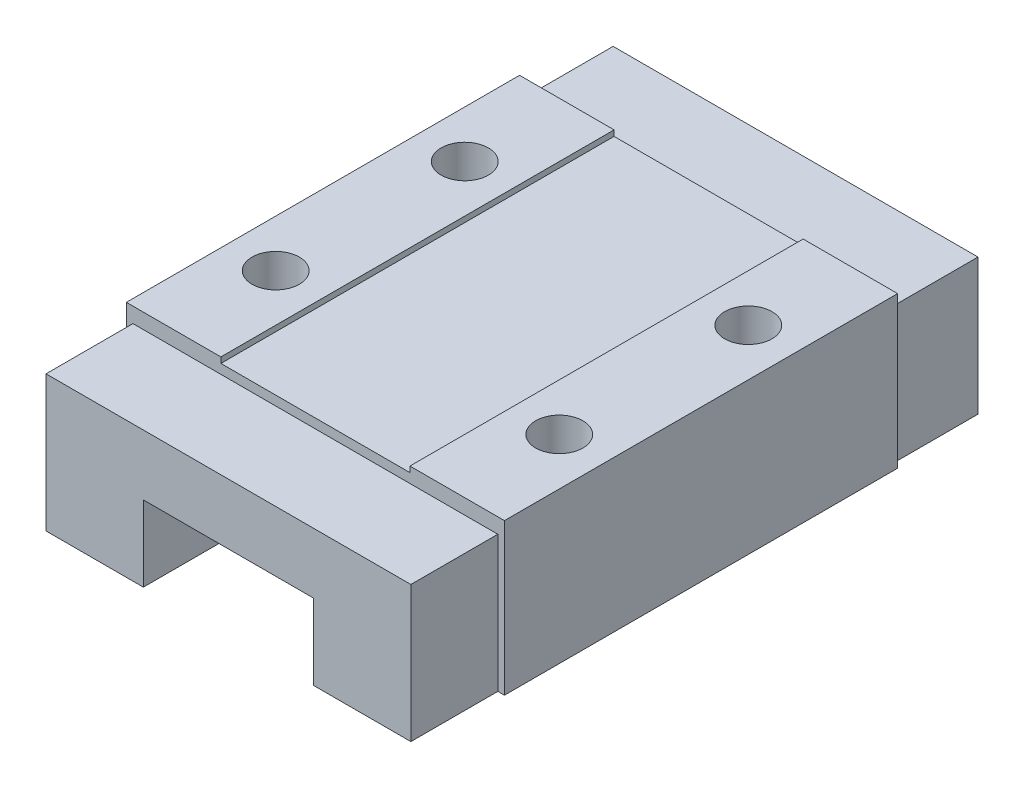
SolidWorks part; units mm, degrees
ref_plane "Front Plane" through (0, 0, 0) normal (0, 0, 1) x (1, 0, 0)
ref_plane "Top Plane" through (0, 0, 0) normal (0, 1, 0) x (1, 0, 0)
ref_plane "Right Plane" through (0, 0, 0) normal (1, 0, 0) x (0, 0, -1)
sketch "Sketch1" plane through (0, 0, 0) normal (0, 0, 1) x (1, 0, 0)
  line L0 (-10, 0) -> (-5, 0)
  line L1 (-5, 0) -> (-5, -0.3)
  line L2 (-5, -0.3) -> (5, -0.3)
  line L3 (5, -0.3) -> (5, 0)
  line L4 (5, 0) -> (10, 0)
  line L5 (10, 0) -> (10, -8)
  line L6 (10, -8) -> (4.5, -8)
  line L7 (4.5, -8) -> (4.5, -4)
  line L8 (4.5, -4) -> (-4.5, -4)
  line L9 (-4.5, -4) -> (-4.5, -8)
  line L10 (-4.5, -8) -> (-10, -8)
  line L11 (-10, -8) -> (-10, 0)
  point P3 (0, -0.3)
  point P15 (0, -4)
  dimension "D1" = 20
  dimension "D2" = 5
  dimension "D3" = 0.3
  dimension "D4" = 8
  dimension "D5" = 4
  dimension "D6" = 9
extrude "Boss-Extrude1" add sketch "Sketch1" along normal mid plane 20.8
sketch "Sketch2" plane through (0, 0, 0) normal (0, 0, 1) x (1, 0, 0)
  line L0 (-9.65, -0.8) -> (9.65, -0.8)
  line L1 (9.65, -0.8) -> (9.65, -8)
  line L2 (9.65, -8) -> (4.5, -8)
  line L3 (4.5, -4) -> (4.5, -8) construction
  line L4 (4.5, -8) -> (4.5, -4)
  line L5 (4.5, -4) -> (-4.5, -4)
  line L6 (-4.5, -4) -> (-4.5, -8)
  line L7 (-4.5, -8) -> (-4.5, -4) construction
  line L8 (-4.5, -8) -> (-9.65, -8)
  line L9 (-9.65, -8) -> (-9.65, -0.8)
  line L10 (-10, -8) -> (-4.5, -8) construction
  line L11 (4.5, -8) -> (10, -8) construction
  point P16 (0, -0.8)
  dimension "D1" = 19.3
  dimension "D2" = 7.2
extrude "Boss-Extrude2" add sketch "Sketch2" along normal mid plane 30
hole_wizard "Tap Drill for M3 Tap1" positions "Sketch3" profile "Sketch4" hole size "M3" standard "ISO"
sketch "Sketch3" plane through (0, 0, 0) normal (0, 1, 0) x (1, 0, 0)
  line L0 (0, 9.1892) -> (0, -8.2377) construction
  line L2 (9.0333, 0) -> (-8.8497, 0) construction
  point P0 (7.5, 5)
  point P2 (7.5, -5)
  point P4 (-7.5, 5)
  point P6 (-7.5, -5)
  dimension "D1" = 15
  dimension "D2" = 10
sketch "Sketch4" plane through (7.5, 0, -5) normal (1, 0, 0) x (0, 0, 1)
  line L0 (0, 0) -> (0, 3.7511)
  line L1 (0, 3.7511) -> (1.25, 3)
  line L2 (1.25, 3) -> (1.25, 0)
  line L5 (1.25, 0) -> (0, 0)
  line L10 (0, 3.7511) -> (-1.25, 3) construction
  line L11 (0, -6.35) -> (0, 107.95) construction
  dimension "Hole Dia." = 2.5
  dimension "Hole Depth" = 3
  dimension "Drill Angle" = 118
